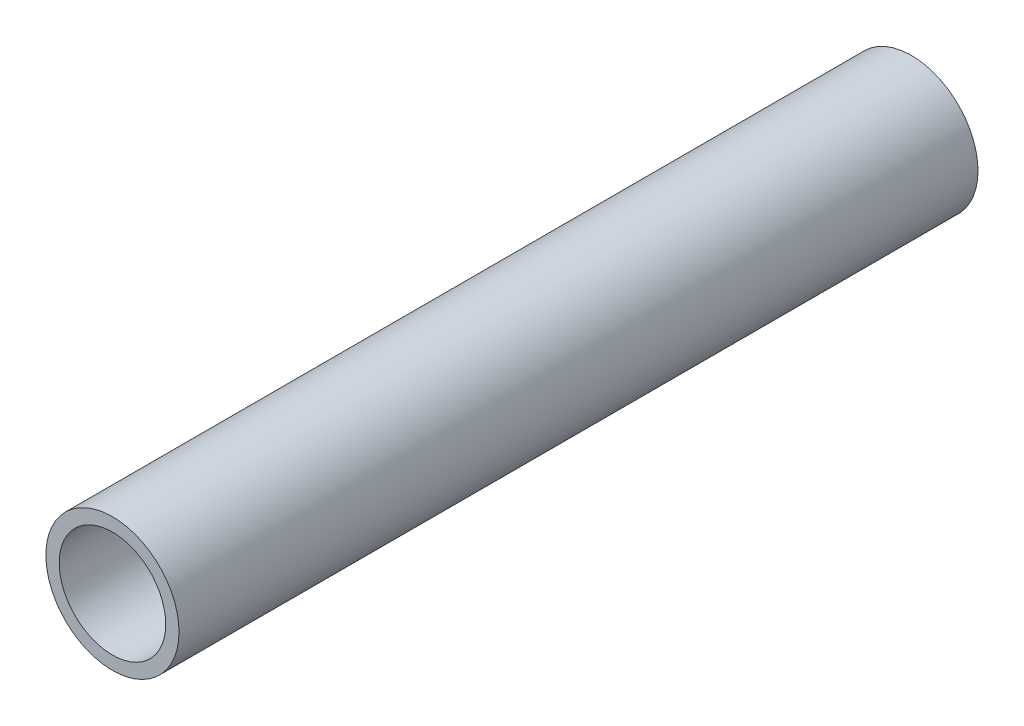
SolidWorks part; units mm, degrees
ref_plane "Plano frontal" through (0, 0, 0) normal (0, 0, 1) x (1, 0, 0)
ref_plane "Plano superior" through (0, 0, 0) normal (0, 1, 0) x (1, 0, 0)
ref_plane "Plano direito" through (0, 0, 0) normal (1, 0, 0) x (0, 0, -1)
sketch "Esboço1" plane through (0, 0, 0) normal (0, 0, 1) x (1, 0, 0)
  circle A0 centre (0, 0) radius 12.5
  circle A1 centre (0, 0) radius 10
  dimension "D1" = 25
  dimension "D2" = 20
extrude "Ressalto-extrusão1" add sketch "Esboço1" along normal blind 150
